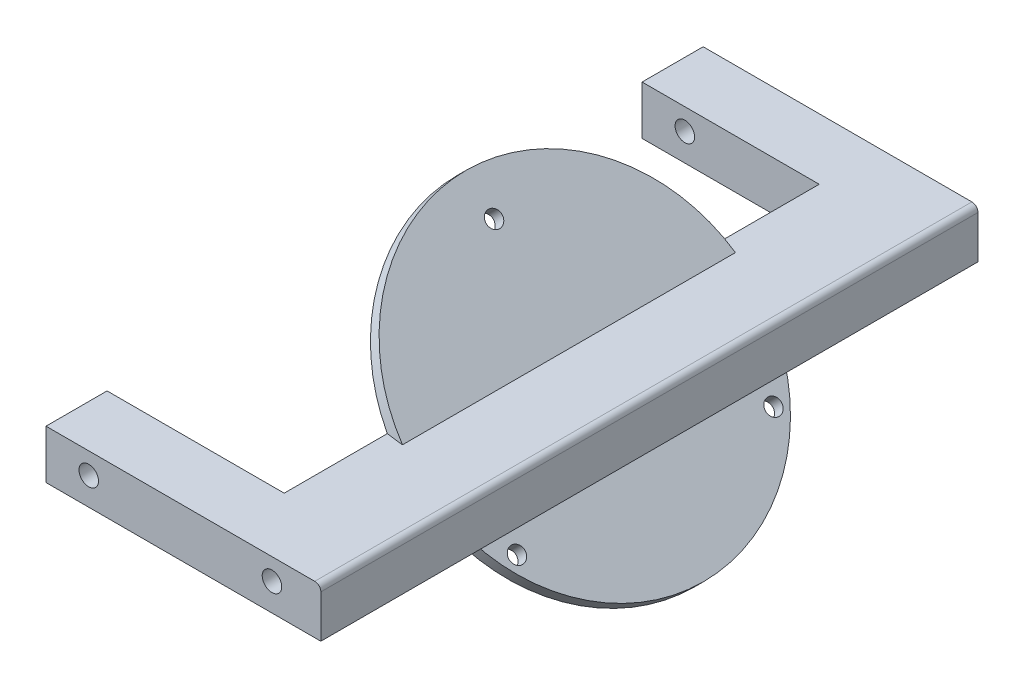
SolidWorks part; units mm, degrees
material "Nylon 101"
ref_plane "Front Plane" through (0, 0, 0) normal (0, 0, 1) x (1, 0, 0)
ref_plane "Top Plane" through (0, 0, 0) normal (0, 1, 0) x (1, 0, 0)
ref_plane "Right Plane" through (0, 0, 0) normal (1, 0, 0) x (0, 0, -1)
sketch "Sketch1" plane through (0, 0, 0) normal (0, 0, 1) x (1, 0, 0)
  line L4 (8, 4) -> (-8, 4)
  line L6 (0, -4) -> (-8, 4)
  line L7 (0, 4) -> (0, -4) construction
  line L8 (8, 4) -> (8, -4)
  line L9 (8, -4) -> (0, -4)
  dimension "D1" = 8
  dimension "D2" = 45
extrude "Base" add sketch "Sketch1" along normal mid plane 107.6
sketch "Sketch4" plane through (-2, -2, 0) normal (-0.7071, -0.7071, 0) x (0, 0, 1)
  line L0 (-53.8, 2.8284) -> (53.8, 2.8284) construction
  line L1 (-53.8, 8.4853) -> (-53.8, -2.8284) construction
  line L2 (53.8, 8.4853) -> (53.8, -2.8284) construction
  line L3 (0, 8.4853) -> (0, -2.8284) construction
  line L4 (53.8, 8.4853) -> (-53.8, 8.4853) construction
  line L6 (53.8, -2.8284) -> (-53.8, -2.8284) construction
  line L7 (-17.5, 20.3284) -> (17.5, 20.3284)
  line L8 (-17.5, 20.3284) -> (-17.5, -14.6716)
  line L9 (-17.5, -14.6716) -> (17.5, -14.6716)
  line L10 (17.5, 20.3284) -> (17.5, -14.6716)
  line L11 (-17.5, 20.3284) -> (17.5, -14.6716) construction
  line L12 (-17.5, -14.6716) -> (17.5, 20.3284) construction
  circle A0 centre (0, 2.8284) radius 27.5
  point P16 (0, 2.8284)
  point P17 (0, 2.8284)
  dimension "D1" = 55
  dimension "D2" = 35
extrude "Boss-Extrude2" add sketch "Sketch4" against normal blind 2
hole_wizard "M2 Clearance Hole1" positions "Sketch5" profile "Sketch6" hole size "M2" standard "ANSI Metric" end condition through all
sketch "Sketch5" plane through (-0.5858, -0.5858, 0) normal (0.7071, 0.7071, 0) x (0.7071, -0.7071, 0)
  line L4 (-8.4853, 0) -> (2.8284, 0) construction
  line L5 (-20.3284, 17.5) -> (-20.3284, -17.5) construction
  line L6 (-20.3284, -17.5) -> (14.6716, -17.5) construction
  line L7 (14.6716, 17.5) -> (14.6716, -17.5) construction
  line L8 (-20.3284, 17.5) -> (14.6716, 17.5) construction
  point P0 (-23.8284, 0)
  point P2 (11.1716, 21)
  point P4 (11.1716, -21)
  dimension "D1" = 3.5
  dimension "D2" = 3.5
  dimension "D3" = 3.5
  dimension "D4" = 3.5
sketch "Sketch6" plane through (-17.435, 16.2635, 0) normal (0, 0, 1) x (-0.7071, 0.7071, 0)
  line L0 (0, 0) -> (0, 29.5)
  line L1 (0, 29.5) -> (1.3, 29.5)
  line L2 (1.3, 29.5) -> (1.3, 0)
  line L5 (1.3, 0) -> (0, 0)
  line L11 (0, -6.35) -> (0, 107.95) construction
  dimension "Thru Hole Dia." = 2.6
  dimension "Thru Hole Depth" = 29.5
ref_plane "Plane1" through (-2, 2, 0) normal (0.7071, -0.7071, 0) x (0, 0, 1)
sketch "Sketch8" plane through (-2, 2, 0) normal (0.7071, -0.7071, 0) x (0, 0, 1)
  line L0 (0, 3.8284) -> (0, 2.8284)
  line L1 (27.5, 2.8284) -> (-27.5, 2.8284) construction
  line L2 (0, 2.8284) -> (-12, 2.8284)
  line L4 (0, 2.8284) -> (0, 10.3284) construction
  line L5 (-6.5, 10.3284) -> (-12, 2.8284)
  arc A1 (-6.5, 10.3284) -> (0, 3.8284) centre (0, 10.3284) ccw
  dimension "D2" = 6.5
  dimension "D1" = 1
  dimension "D3" = 12
revolve "Revolve1" add sketch "Sketch8" angle 360 about L4
fillet "Fillet1" radius 0.5 1 edges at (-13.8995, -0.7071, 0)
hole_wizard "Side Holes" positions "Sketch2" profile "Sketch3" hole size "Ø3.2" standard "ANSI Metric" end condition through all
sketch "Sketch2" plane through (0, 0, 53.8) normal (0, 0, 1) x (1, 0, 0)
  line L0 (0, 0.5) -> (0, 4) construction
  line L1 (8, 4) -> (-8, 4) construction
  line L3 (-4.5, 0.5) -> (8, 0.5) construction
  line L4 (-8, 4) -> (0, -4) construction
  line L6 (8, -4) -> (8, 4) construction
  point P0 (0, 0.5)
  dimension "D1" = 3.5
sketch "Sketch3" plane through (0, 0.5, 53.8) normal (1, 0, 0) x (0, -1, 0)
  line L0 (0, 0) -> (0, 107.6)
  line L1 (0, 107.6) -> (1.6, 107.6)
  line L2 (1.6, 107.6) -> (1.6, 0)
  line L5 (1.6, 0) -> (0, 0)
  line L11 (0, -6.35) -> (0, 107.95) construction
  dimension "Thru Hole Dia." = 3.2
  dimension "Thru Hole Depth" = 107.6
sketch "Sketch9" plane through (0, 0, 53.8) normal (0, 0, 1) x (1, 0, 0)
  line L0 (-8, 4) -> (0, -4)
  line L1 (0, -4) -> (-37, -4)
  line L2 (-37, -4) -> (-37, 4)
  line L3 (-37, 4) -> (-8, 4)
  line L4 (8, -4) -> (8, 4) construction
  dimension "D1" = 45
extrude "Side Arm" add sketch "Sketch9" against normal blind 10
mirror "Mirror1" about plane through (0, 0, 0) normal (0, 0, 1) of "Side Arm"
hole_wizard "Ø3.2 (3.2) Diameter Hole1" positions "Sketch10" profile "Sketch11" hole size "Ø3.2" standard "ANSI Metric" end condition through all
sketch "Sketch10" plane through (0, 0, 53.8) normal (0, 0, 1) x (1, 0, 0)
  line L0 (-37, 4) -> (-37, -4) construction
  point P0 (-30, 0.5)
  dimension "D1" = 7
sketch "Sketch11" plane through (-30, 0.5, 53.8) normal (1, 0, 0) x (0, -1, 0)
  line L0 (0, 0) -> (0, 107.6)
  line L1 (0, 107.6) -> (1.6, 107.6)
  line L2 (1.6, 107.6) -> (1.6, 0)
  line L5 (1.6, 0) -> (0, 0)
  line L11 (0, -6.35) -> (0, 107.95) construction
  dimension "Thru Hole Dia." = 3.2
  dimension "Thru Hole Depth" = 107.6
fillet "Fillet2" radius 1 1 edges at (8, 4, 0)
